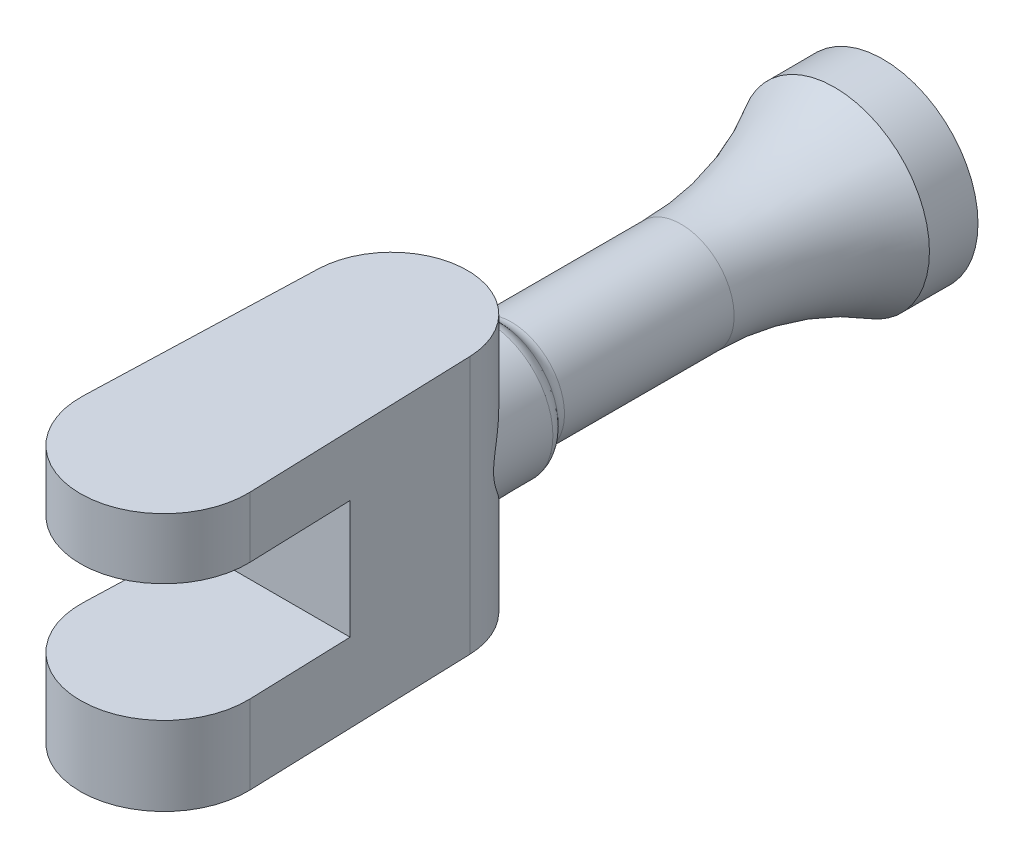
SolidWorks part; units mm, degrees
ref_plane "前基準面" through (0, 0, 0) normal (0, 0, 1) x (1, 0, 0)
ref_plane "上基準面" through (0, 0, 0) normal (0, 1, 0) x (1, 0, 0)
ref_plane "右基準面" through (0, 0, 0) normal (1, 0, 0) x (0, 0, -1)
sketch "草圖1" plane through (0, 0, 0) normal (0, 0, 1) x (1, 0, 0)
  circle A0 centre (0, 0) radius 62.5
  dimension "D1" = 125
extrude "填料-伸長1" add sketch "草圖1" along normal blind 32
ref_plane "平面1" through (0, 0, 195) normal (0, 0, -1) x (-1, 0, 0)
sketch "草圖2" plane through (0, 0, 195) normal (0, 0, -1) x (-1, 0, 0)
  circle A0 centre (0, 0) radius 35
  dimension "D1" = 70
sketch "草圖3" plane through (0, 0, 0) normal (0, 1, 0) x (1, 0, 0)
  line L0 (0, -32) -> (0, -245)
  line L1 (-62.5, -32) -> (62.5, -32) construction
  line L3 (0, -245) -> (35, -245)
  line L5 (35, -245) -> (35, -133.211)
  line L6 (62.5, -32) -> (0, -32)
  line L7 (62.5, 0) -> (-62.5, 0) construction
  arc A0 (35, -133.211) -> (62.5, -32) centre (234.9985, -133.211) cw
  dimension "D2" = 111.789
  dimension "D1" = 35
  dimension "D3" = 245
  dimension "D4" = 101.211
revolve "旋轉1" add sketch "草圖3" angle 360 about L0
ref_plane "平面2" through (0, 0, 211.16) normal (0, 0, -1) x (-1, 0, 0)
sketch "草圖5" plane through (0, 0, 211.16) normal (0, 0, -1) x (-1, 0, 0)
  circle A0 centre (0, 0) radius 44
  dimension "D1" = 88
sketch "草圖6" plane through (0, 0, 0) normal (0, 1, 0) x (1, 0, 0)
  line L1 (0, -245) -> (35, -245)
  line L2 (-35, -245) -> (35, -245) construction
  line L3 (0, -203.08) -> (78.5179, -203.08) construction
  line L4 (43.52, -261.16) -> (0, -261.16)
  line L6 (43.5179, -211.16) -> (0, -211.16) construction
  line L7 (0, -261.16) -> (0, -245)
  line L8 (0, -211.16) -> (0, -195) construction
  line L9 (0, -195) -> (35, -195) construction
  line L10 (43.5179, -211.16) -> (43.52, -261.16) construction
  line L11 (0, -253.08) -> (77.7283, -253.08) construction
  arc A2 (43.5179, -211.16) -> (39.2589, -203.08) centre (30.703, -212.7522) ccw construction
  arc A3 (39.2589, -203.08) -> (35, -195) centre (47.8149, -193.4078) cw construction
  arc A4 (35, -245) -> (38.8641, -253.08) centre (45.3798, -245) ccw
  arc A5 (38.8641, -253.08) -> (43.52, -261.16) centre (30.7581, -263.1323) cw
  dimension "D1" = 12.9134
  dimension "D2" = 47.8149
  dimension "D4" = 43.52
  dimension "D3" = 43.5179
  dimension "D5" = 16.16
  dimension "D6" = 9.6722
  dimension "D8" = 8.08
revolve "旋轉2" add sketch "草圖6" angle 360 about L8
sketch "草圖9" plane through (0, 0, 0) normal (0, 1, 0) x (1, 0, 0)
  line L1 (0, -261.16) -> (0, -322.34)
  line L3 (43.52, -261.16) -> (0, -261.16)
  line L5 (0, -322.34) -> (46.1833, -322.34)
  line L7 (-43.52, -261.16) -> (43.52, -261.16) construction
  line L8 (0, 0) -> (0, -322.34) construction
  line L9 (62.5, 0) -> (-62.5, 0) construction
  arc A1 (46.1833, -322.34) -> (43.52, -261.16) centre (617.1193, -266.8382) cw
  arc A2 (43.52, -261.16) -> (38.8641, -253.08) centre (30.7581, -263.1323) ccw construction
  dimension "D1" = 573.6274
  dimension "D2" = 46.1833
  dimension "D3" = 61.18
revolve "旋轉3" add sketch "草圖9" angle 360 about L8
sketch "草圖10" plane through (0, 0, 0) normal (0, 1, 0) x (0, 0, -1)
  line L0 (-245, 35) -> (-245, -35) construction
  line L1 (-245, -35) -> (-133.211, -35) construction
  line L2 (-245, 35) -> (-245, -35) construction
  line L3 (-245, -35) -> (-133.211, -35) construction
  line L4 (-95.0324, 0) -> (-223.608, 0) construction
  line L6 (-322.3333, 49.9722) -> (-472.1667, 54.9694)
  line L7 (-322.3333, -49.9722) -> (-472.1667, -54.9694)
  arc A0 (-322.3333, -49.9722) -> (-322.3333, 49.9722) centre (-324, 0) ccw
  arc A1 (-472.1667, 54.9694) -> (-472.1667, -54.9694) centre (-474, 0) ccw
  dimension "D2" = 100
  dimension "D3" = 110
  dimension "D1" = 79
  dimension "D4" = 150
  dimension "D5" = 35
extrude "填料-伸長2" add sketch "草圖10" against normal blind 91 and the other way blind 79
ref_point "點1"
sketch "草圖11" plane through (0, 0, 0) normal (0, 1, 0) x (0, 0, -1)
  line L0 (-253.08, 38.8641) -> (-253.08, -38.8641) construction
  line L1 (-261.16, 43.52) -> (-261.16, -43.52) construction
  line L2 (-472.1667, -54.9694) -> (-322.3333, -49.9722) construction
  line L3 (-322.3333, 49.9722) -> (-472.1667, 54.9694) construction
  line L4 (-245, 35) -> (-245, -35) construction
  line L5 (-133.211, 35) -> (-133.211, -35) construction
  line L6 (-32, 62.5) -> (-32, -62.5) construction
  line L7 (0, -62.5) -> (0, 62.5) construction
  line L8 (-253.08, 38.8641) -> (-253.08, -38.8641)
  line L9 (-261.16, 43.52) -> (-261.16, -43.52)
  line L10 (-472.1667, -54.9694) -> (-322.3333, -49.9722)
  line L11 (-322.3333, 49.9722) -> (-472.1667, 54.9694)
  line L12 (-245, 35) -> (-245, -35)
  line L13 (-133.211, 35) -> (-133.211, -35)
  line L14 (-32, 62.5) -> (-32, -62.5)
  line L15 (0, -62.5) -> (0, 62.5)
  line L16 (0, 0) -> (-474, 0) construction
  line L17 (-32, -62.5) -> (0, -62.5) construction
  arc A0 (-301.2509, 44.5251) -> (-261.16, 43.52) centre (-266.8382, 617.1193) ccw construction
  arc A1 (-261.16, -43.52) -> (-301.2509, -44.5251) centre (-266.8382, -617.1193) ccw construction
  arc A2 (-472.1667, 54.9694) -> (-472.1667, -54.9694) centre (-474, 0) ccw construction
  arc A3 (-322.3333, -49.9722) -> (-322.3333, 49.9722) centre (-324, 0) ccw construction
  arc A4 (-301.2509, 44.5251) -> (-261.16, 43.52) centre (-266.8382, 617.1193) ccw
  arc A5 (-261.16, -43.52) -> (-301.2509, -44.5251) centre (-266.8382, -617.1193) ccw
  arc A6 (-472.1667, 54.9694) -> (-472.1667, -54.9694) centre (-474, 0) ccw
  arc A7 (-322.3333, -49.9722) -> (-322.3333, 49.9722) centre (-324, 0) ccw
  point P17 (-529, 0)
  dimension "D1" = 32
  dimension "D2" = 101.211
  dimension "D3" = 111.789
  dimension "D4" = 79
  dimension "D5" = 150
  dimension "D6" = 62.5
  dimension "D7" = 529
sketch "草圖12" plane through (0, 0, 0) normal (1, 0, 0) x (0, -1, 0)
  line L0 (-79, -529) -> (91, -529) construction
  line L1 (39, -529) -> (-39, -529)
  line L2 (39, -529) -> (39, -404)
  line L3 (39, -404) -> (-39, -404)
  line L4 (-39, -529) -> (-39, -404)
  line L6 (91, -529) -> (91, -472.1667) construction
  line L7 (0, -133.211) -> (0, -577.6352) construction
  line L8 (-35, -133.211) -> (35, -133.211) construction
  line L10 (91, -472.1667) -> (91, -322.3333) construction
  line L11 (-79, -472.1667) -> (-79, -529) construction
  line L12 (-79, -472.1667) -> (-79, -322.3333) construction
  dimension "D1" = 40
  dimension "D2" = 78
  dimension "D3" = 52
  dimension "D4" = 125
  dimension "D5" = 91
  dimension "D6" = 79
extrude "除料-伸長1" cut sketch "草圖12" against normal through all both and the other way through all
